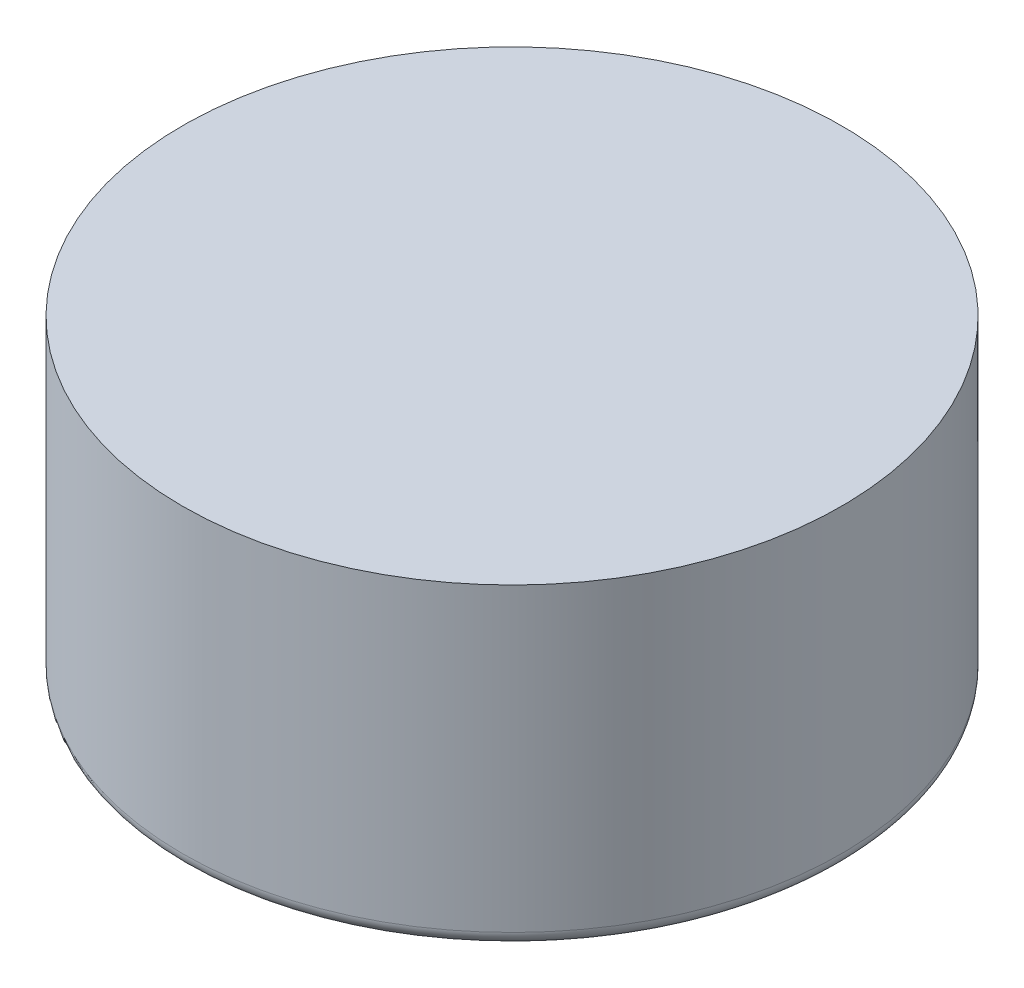
SolidWorks part; units mm, degrees
ref_plane "Front Plane" through (0, 0, 0) normal (0, 0, 1) x (1, 0, 0)
ref_plane "Top Plane" through (0, 0, 0) normal (0, 1, 0) x (1, 0, 0)
ref_plane "Right Plane" through (0, 0, 0) normal (1, 0, 0) x (0, 0, -1)
sketch "Sketch1" plane through (0, 0, 0) normal (0, 1, 0) x (1, 0, 0)
  circle A0 centre (0, 0) radius 11.5
  dimension "D1" = 23
extrude "Boss-Extrude1" add sketch "Sketch1" along normal mid plane 11
sketch "Sketch2" plane through (0, -5.5, 0) normal (0, -1, 0) x (1, 0, 0)
  circle A0 centre (0, 0) radius 1
  dimension "D1" = 2
extrude "Boss-Extrude2" add sketch "Sketch2" along normal mid plane 6.5
fillet "Fillet1" radius 0.5 1 edges at (0, -5.5, 11.5)
